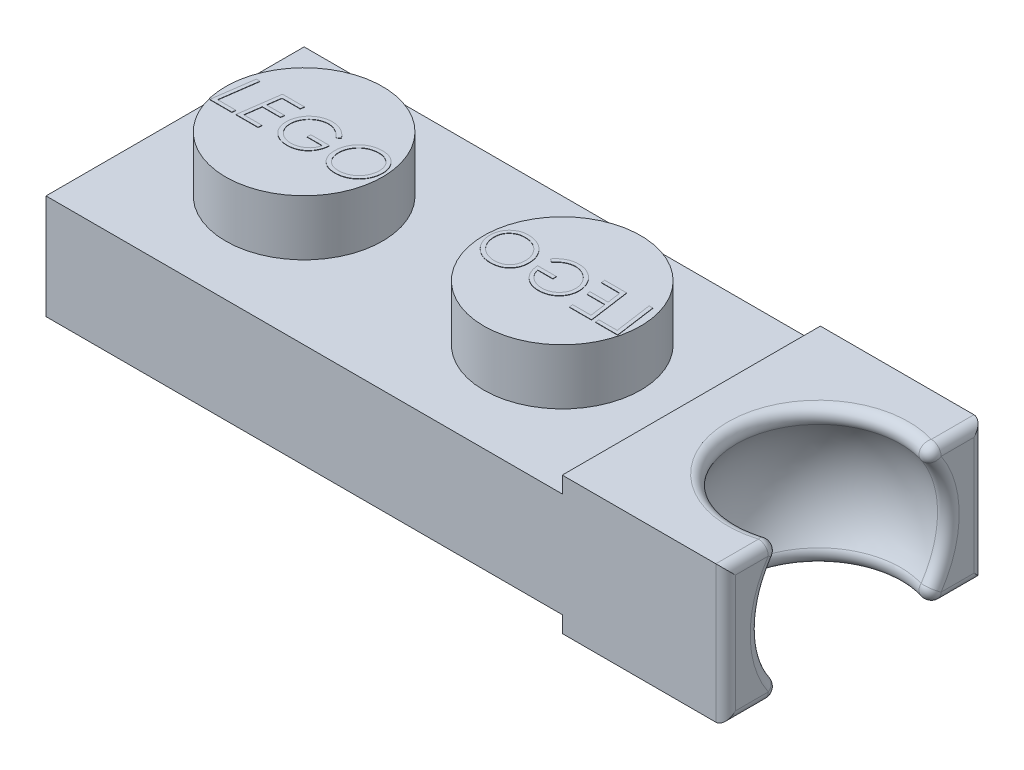
SolidWorks part; units mm, degrees
ref_plane "Front Plane" through (0, 0, 0) normal (0, 0, 1) x (1, 0, 0)
ref_plane "Top Plane" through (0, 0, 0) normal (0, 1, 0) x (1, 0, 0)
ref_plane "Right Plane" through (0, 0, 0) normal (1, 0, 0) x (0, 0, -1)
sketch "Sketch1" plane through (0, 0, 0) normal (0, 1, 0) x (1, 0, 0)
  line L0 (0, 0) -> (7.9, 0)
  line L1 (7.9, 0) -> (7.9, 7.9)
  line L2 (0, 0) -> (0, 7.9)
  line L3 (0, 7.9) -> (7.9, 7.9)
  dimension "D1" = 7.9
  dimension "D2" = 7.9
  dimension "D3" = 7.9
extrude "Boss-Extrude1" add sketch "Sketch1" along normal blind 3.2
sketch "Sketch2" plane through (0, 3.2, 0) normal (0, 1, 0) x (1, 0, 0)
  line L0 (0, 7.9) -> (7.9, 0) construction
  circle A0 centre (3.95, 3.95) radius 2.4
extrude "Boss-Extrude2" add sketch "Sketch2" along normal blind 1.7
sketch "Sketch3" plane through (0, 4.9, 0) normal (0, 1, 0) x (1, 0, 0)
  line L0 (1.625, 3.3549) -> (6.275, 3.3549) construction
  circle A0 centre (3.95, 3.95) radius 2.4 construction
  circle A1 centre (3.95, 3.95) radius 2.4 construction
  text T0 "<i>LEGO</i>" font "Century Gothic" height 1.25
extrude "Boss-Extrude4" add sketch "Sketch3" along normal blind 0.01
sketch "Sketch4" plane through (0, 0, 0) normal (0, -1, 0) x (1, 0, 0)
  line L0 (7.9, -7.9) -> (0, -7.9) construction
  line L1 (7.3, -7.3) -> (0.6204, -7.3)
  line L2 (7.3, -7.3) -> (7.3, -0.6204)
  line L3 (7.3, -0.6204) -> (0.6204, -0.6204)
  line L4 (0.6204, -7.3) -> (0.6204, -0.6204)
  line L5 (7.9, 0) -> (7.9, -7.9) construction
  dimension "D1" = 0.6
  dimension "D2" = 0.6
extrude "Cut-Extrude1" cut sketch "Sketch4" against normal blind 2.01 contours L2 L1 L4 L3
sketch "Sketch5" plane through (0, 3.2, 0) normal (0, 1, 0) x (1, 0, 0)
  line L1 (1.4581, 1.5578) -> (6.3695, 1.5578)
  line L2 (1.4581, 1.5578) -> (1.4581, 6.3652)
  line L3 (1.4581, 6.3652) -> (6.3695, 6.3652)
  line L4 (6.3695, 1.5578) -> (6.3695, 6.3652)
  circle A1 centre (6.3695, 6.3652) radius 1.0161
  circle A2 centre (6.3695, 1.5578) radius 1.0061
  circle A3 centre (1.4581, 1.5578) radius 1.0219
  circle A4 centre (1.4581, 6.3652) radius 1.0411
  circle M5 centre (3.95, 3.95) radius 2.4
extrude "Boss-Extrude5" add sketch "Sketch5" against normal blind 2.01 contours L1 A2 L4 | L2 A3 L1 | L1 A3 L2 | L4 A2 L1 M5 | L4 A1 L3 | L3 A1 L4 | L2 A4 L3 | L3 A4 L2
mirror "Mirror1" about plane through (7.9, 3.2, 0) normal (-1, 0, 0) of bodies 106
sketch "Sketch6" plane through (15.8, 0, 0) normal (1, 0, 0) x (0, 0, -1)
  line L0 (7.9, 3.2) -> (7.9, 0) construction
  line L1 (0, -0.5) -> (7.9, -0.5)
  line L2 (0, -0.5) -> (0, 3.7)
  line L3 (0, 3.7) -> (7.9, 3.7)
  line L4 (7.9, -0.5) -> (7.9, 3.7)
  line L5 (0, 3.2) -> (0, 0) construction
  line L6 (7.9, 0) -> (0, 0) construction
  line L7 (7.9, 3.2) -> (0, 3.2) construction
  dimension "D1" = 0.5
  dimension "D2" = 0.5
extrude "Boss-Extrude6" add sketch "Sketch6" along normal blind 5
ref_plane "Plane1" through (0, 1.6, 0) normal (0, 1, 0) x (1, 0, 0)
sketch "Sketch13" plane through (0, 1.6, 0) normal (0, 1, 0) x (1, 0, 0)
  line L0 (20.8, 3.95) -> (15.8, 3.95) construction
  line L1 (20.8, 7.9) -> (20.8, 0) construction
  line L2 (15.8, 7.9) -> (15.8, 0) construction
  line L3 (19.6889, 0.95) -> (19.6889, 6.95)
  arc A0 (19.6889, 6.95) -> (19.6889, 0.95) centre (19.6889, 3.95) ccw
revolve "Cut-Revolve1" cut sketch "Sketch13" angle 360 about L3
fillet "Fillet1" radius 0.3 10 edges at (20.8, 3.7, -6.8409) (20.8, 1.6, -7.9) (20.8, -0.5, -6.8409) (20.8, -0.5, -1.0591) (20.8, 3.7, -1.0591) (20.8, 1.6, 0) (17.5465, -0.5, -3.95) (20.8, 1.6, -6.7367) (20.8, 1.6, -1.1633) (17.5465, 3.7, -3.95)
